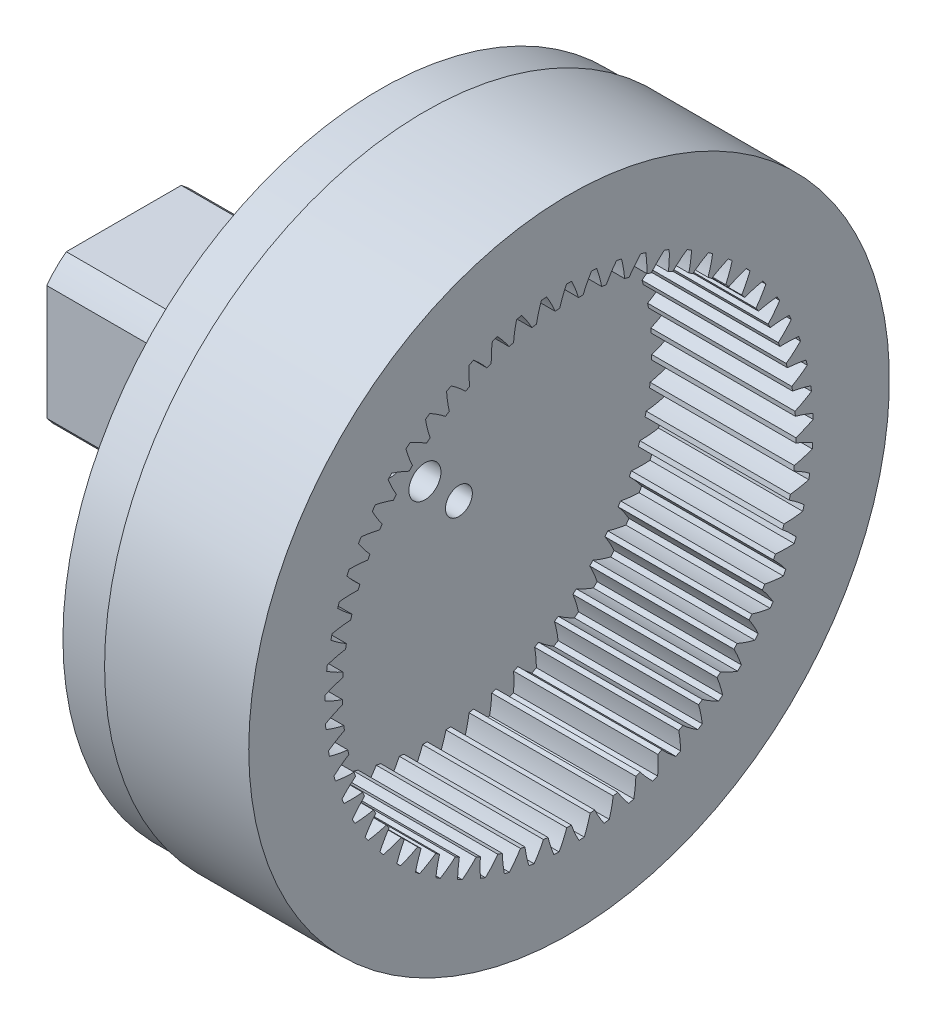
SolidWorks part; units mm, degrees
ref_plane "Plane1" through (0, 0, 0) normal (0, 0, 1) x (1, 0, 0)
ref_plane "Plane2" through (0, 0, 0) normal (0, 1, 0) x (1, 0, 0)
ref_plane "Plane3" through (0, 0, 0) normal (1, 0, 0) x (0, 0, -1)
sketch "HoldingSke" plane through (0, 0, 0) normal (0, 1, 0) x (1, 0, 0)
  line L0 (0, 0) -> (0.404, -0.7288)
  line L1 (-15, 0) -> (100, 0) construction
  line L2 (0, 0) -> (-2.1039, 2.3779)
  line L3 (0, 0) -> (-11.863, 4.5341)
  line L4 (0, 0) -> (4.1868, 7.5532)
  line L5 (0, 0) -> (-23.7986, -8.8762)
  line L6 (0, 0) -> (-10.5278, -7.1032)
  line L7 (-2.1039, 2.3779) -> (3.3635, 27.1825)
  line L8 (-76.2, 3.5779) -> (-54.61, 3.5779)
  line L9 (-71.009, 38.7566) -> (-53.1078, 45.2721)
  line L10 (-76.2, 71.12) -> (104.1128, 71.12)
  line L11 (0, 0) -> (-22.5, 0)
  line L12 (-76.2, 101.6) -> (-76.155, 101.6)
  line L13 (24.9733, 27.94) -> (52.9518, 28.4284)
  line L14 (24.9733, 27.94) -> (24.9743, 27.94)
  line L15 (24.9733, 27.94) -> (100.4006, 29.5858)
  circle A0 centre (0, 0) radius 50
  circle A1 centre (0, 0) radius 12.7
  circle A2 centre (0, 0) radius 12.7
  dimension "MHD" = 25.4
  dimension "Hub_dia" = 25.4
  dimension "Diameter" = 100
  dimension "Num_teeth" = 61
  dimension "Pitch" = 0.8333
  dimension "Overall_len" = 25.4
  dimension "Show_teeth" = 61
  dimension "Thickness" = 12.7
  dimension "OAL" = 25.4001
  dimension "T_dim" = 21.59
  dimension "Ap" = 20
  dimension "H" = 19.05
  dimension "Pitch_radius" = 180.3128
  dimension "Width" = 22.5
  dimension "Backlash" = 0.045
  dimension "Addendum_fac" = 1
  dimension "Dedendum_fac" = 1.25
  dimension "Clearance_fac" = 0.25
  dimension "Dedendum_add" = 0.001
  dimension "Module" = 1.2
sketch "BasProSke" plane through (0, 0, 0) normal (0, 1, 0) x (1, 0, 0)
  line L0 (-10, 0) -> (60, 0) construction
  line L1 (0, 35.4) -> (0, 50)
  line L2 (0, 35.4) -> (22.5, 35.4)
  line L3 (22.5, 35.4) -> (22.5, 50)
  line L4 (22.5, 50) -> (0, 50)
  dimension "Diameter" = 100
  dimension "Thickness" = 22.5
  dimension "Inside_diameter" = 70.8
revolve "Base-Revolve" add sketch "BasProSke" angle 360 about L0
sketch "TooCutSke" plane through (0, 0, 0) normal (1, 0, 0) x (0, 0, -1)
  line L3 (1.0549, 36.5848) -> (1.0549, 53.6633) construction
  line L4 (0, 0) -> (0, 59.563) construction
  line L5 (0, 0) -> (-3.5174, 68.2369) construction
  line L6 (-16.0823, 30.1656) -> (36.1992, 32.8605) construction
  circle A0 centre (0, 0) radius 36.6 construction
  circle A1 centre (0, 0) radius 38.101 construction
  circle A2 centre (0, 0) radius 30.9535 construction
  circle A3 centre (0, 0) radius 35.3746 construction
  arc A4 (1.4697, 35.3441) -> (0.4087, 38.0988) centre (-16.0823, 30.1656) ccw
  arc A5 (1.4697, 35.3441) -> (-1.4697, 35.3441) centre (0, 0) ccw
  arc A6 (0.4087, 38.0988) -> (-0.4087, 38.0988) centre (0, 0) ccw
  arc A7 (-0.4087, 38.0988) -> (-1.4697, 35.3441) centre (16.0823, 30.1656) ccw
  dimension "Pitch_dia" = 73.2
  dimension "Base_dia" = 61.9069
  dimension "Root_dia" = 76.202
  dimension "Overcut_dia" = 70.7492
  dimension "Flank_rad" = 18.3
  dimension "Half_ang" = 2.951
  dimension "Half_CT" = 1.0549
extrude "ToothCut" cut sketch "TooCutSke" along normal through all
fillet "Breaks" [suppressed] radius 0.12
fillet "RootFillets" [suppressed] radius 0.301
pattern_circular "TeethCuts" count 61 every 5.902 about axis through (-10, 0, 0) along (1, 0, 0) of "RootFillets", "Breaks", "ToothCut"
sketch "Sketch1" plane through (0, 0, 0) normal (-1, 0, 0) x (0, 0, 1)
  circle A0 centre (0, 0) radius 49.5
  dimension "D1" = 99
extrude "Boss-Extrude2" add sketch "Sketch1" along normal blind 7
sketch "Sketch2" plane through (-7, 0, 0) normal (-1, 0, 0) x (0, 0, 1)
  circle A0 centre (0, 0) radius 15
  dimension "D1" = 30
extrude "Boss-Extrude3" add sketch "Sketch2" along normal blind 40
sketch "Sketch3" plane through (-47, 0, 0) normal (-1, 0, 0) x (0, 0, 1)
  circle A0 centre (0, 0) radius 2.5
  dimension "D1" = 5
extrude "Cut-Extrude1" cut sketch "Sketch3" against normal up to surface (47 mm away) up to face at (0, 0, 0)
sketch "Sketch4" plane through (-7, 0, 0) normal (-1, 0, 0) x (0, 0, 1)
  circle A0 centre (0, 0) radius 22.5
  circle A1 centre (0, 0) radius 2.5
  dimension "D1" = 45
extrude "Boss-Extrude4" add sketch "Sketch4" along normal blind 1
sketch "Sketch5" plane through (-47, 0, 0) normal (-1, 0, 0) x (0, 0, 1)
  line L1 (-12.0208, 12.0208) -> (12.0208, 12.0208)
  line L2 (-12.0208, 12.0208) -> (-12.0208, -12.0208)
  line L3 (-12.0208, -12.0208) -> (12.0208, -12.0208)
  line L4 (12.0208, 12.0208) -> (12.0208, -12.0208)
  line L5 (-12.0208, 12.0208) -> (12.0208, -12.0208) construction
  line L6 (-12.0208, -12.0208) -> (12.0208, 12.0208) construction
  circle A0 centre (0, 0) radius 17
  circle M2 centre (0, 0) radius 15
  dimension "D1" = 34
extrude "Cut-Extrude2" cut sketch "Sketch5" against normal blind 20 contours L2 M2 | L1 M2 | L4 M2 | L3 M2
sketch "Sketch6" plane through (-47, 0, 0) normal (-1, 0, 0) x (0, 0, 1)
  line L0 (0, 0) -> (-10.6066, -10.6066) construction
  line L1 (0, 0) -> (10.6066, 10.6066) construction
  arc A0 (-12.0208, -8.9722) -> (-8.9722, -12.0208) centre (0, 0) ccw construction
  arc A1 (12.0208, 8.9722) -> (8.9722, 12.0208) centre (0, 0) ccw construction
  circle A2 centre (5.3033, 5.3033) radius 2.1
  circle A3 centre (-5.3033, -5.3033) radius 2.1
  dimension "D1" = 4.2
extrude "Cut-Extrude3" cut sketch "Sketch6" against normal through all
equation "' \"Module@HoldingSke\" = 6.35"
equation "' \"Num_teeth@HoldingSke\" = 24"
equation "' \"Ap@HoldingSke\" =  14.5"
equation "' \"Ap@HoldingSke\" = 14.5"
equation "' \"Width@HoldingSke\" = 12"
equation "' \"Diameter@HoldingSke\" = 8 * 25.4"
equation "' \"Show_teeth@HoldingSke\" = 100"
equation "' \"Backlash@HoldingSke\" = 0.009 * 25.4"
equation "' \"Addendum_fac@HoldingSke\" = 1.0"
equation "' \"Dedendum_fac@HoldingSke\" = 1.25"
equation "' \"Dedendum_add@HoldingSke\" = 0.00005 * 25.4"
equation "' \"Clearance_fac@HoldingSke\" = 0.25"
equation "\"Pitch@HoldingSke\" = 1 / \"Module@HoldingSke\" "
equation "\"Overcut_dia@TooCutSke\" = (\"Num_teeth@HoldingSke\" - 2 * \"Addendum_fac@HoldingSke\") / \"Pitch@HoldingSke\" - 0.002 * 25.4"
equation "\"Pitch_dia@TooCutSke\" = \"Num_teeth@HoldingSke\" / \"Pitch@HoldingSke\""
equation "\"Base_dia@TooCutSke\" = \"Num_teeth@HoldingSke\" / \"Pitch@HoldingSke\" * cos((\"Ap@HoldingSke\"  * 3.14159265 / 180)) * 0.90"
equation "\"Root_dia@TooCutSke\" = \"Num_teeth@HoldingSke\"  / \"Pitch@HoldingSke\" + 2 *  \"Dedendum_fac@HoldingSke\"/ \"Pitch@HoldingSke\" + \"Dedendum_add@HoldingSke\" * 2"
equation "\"Half_ang@TooCutSke\" = 180 / \"Num_teeth@HoldingSke\""
equation "\"Half_CT@TooCutSke\" = \"Num_teeth@HoldingSke\" / \"Pitch@HoldingSke\" * sin((3.14159265 / 2 / \"Num_teeth@HoldingSke\")) / 2 + 10 * \"Backlash@HoldingSke\" / 4"
equation "\"Flank_rad@TooCutSke\" = \"Num_teeth@HoldingSke\" / \"Pitch@HoldingSke\" / 4"
equation "\"Radius@RootFillets\"= \"Clearance_fac@HoldingSke\" / \"Pitch@HoldingSke\" + \"Dedendum_add@HoldingSke\""
equation "\"Break_rad@Breaks\" = 0.02 / \"Pitch@HoldingSke\" * 5"
equation "\"Num_teeth@TeethCuts\" = int( \"Show_teeth@HoldingSke\" ) + 1"
equation "\"Num_teeth@TeethCuts\" = ((sgn( \"Num_teeth@TeethCuts\" - \"Num_teeth@HoldingSke\" )-1)*( \"Num_teeth@TeethCuts\" - \"Num_teeth@HoldingSke\" ))/-2+ \"Num_teeth@HoldingSke\""
equation "\"Num_teeth@TeethCuts\" = ((sgn( \"Num_teeth@TeethCuts\" - 2.0)+1)*( \"Num_teeth@TeethCuts\" - 2.0))/2 +2.0"
equation "\"Angle@TeethCuts\" = 360.0 / \"Num_teeth@HoldingSke\""
equation "\"Diameter@BasProSke\" = \"Num_teeth@HoldingSke\"  / \"Pitch@HoldingSke\" + 2 *  \"Dedendum_fac@HoldingSke\"/ \"Pitch@HoldingSke\" + \"Dedendum_add@HoldingSke\" * 2 + 0.002 * 25.4"
equation "\"Diameter@BasProSke\" = ((sgn( \"Diameter@BasProSke\"  - \"Diameter@HoldingSke\" )+1)*( \"Diameter@BasProSke\"  - \"Diameter@HoldingSke\" ))/2 + \"Diameter@HoldingSke\""
equation "\"Inside_diameter@BasProSke\" =  (\"Num_teeth@HoldingSke\" - 2 * \"Addendum_fac@HoldingSke\") / \"Pitch@HoldingSke\" "
equation "\"Thickness@BasProSke\"  = \"Width@HoldingSke\""
